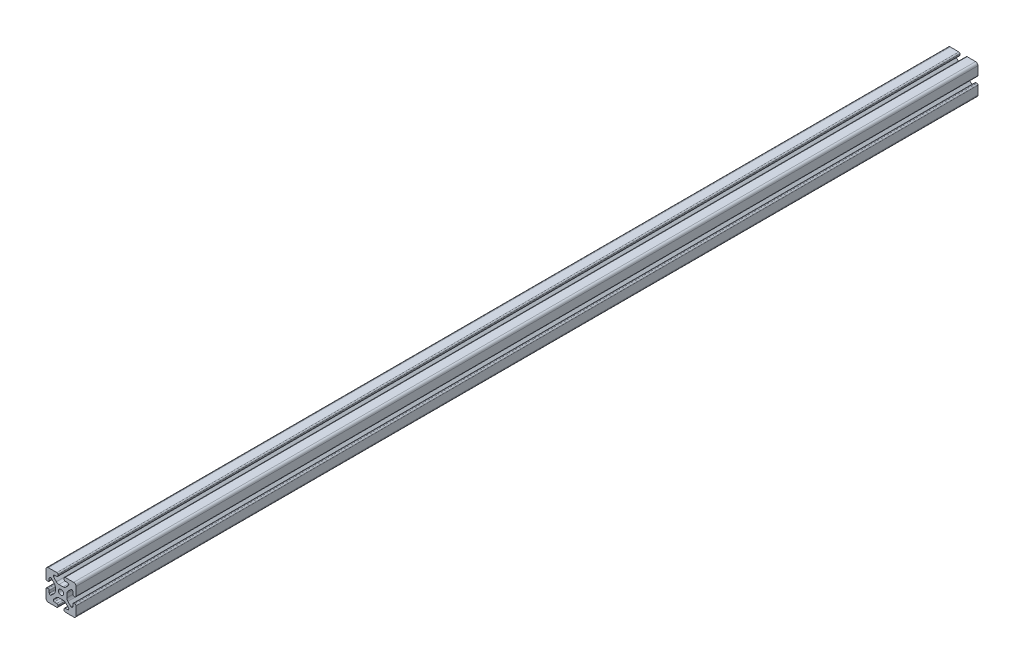
SolidWorks part; units mm, degrees
material "6061 Alloy"
ref_plane "Front Plane" through (0, 0, 0) normal (0, 0, 1) x (1, 0, 0)
ref_plane "Top Plane" through (0, 0, 0) normal (0, 1, 0) x (1, 0, 0)
ref_plane "Right Plane" through (0, 0, 0) normal (1, 0, 0) x (0, 0, -1)
sketch "Sketch1" plane through (0, 0, 0) normal (0, 0, 1) x (1, 0, 0)
  line L0 (0, 19.7407) -> (0, -19.7407) construction
  line L1 (19.0335, 0) -> (-20.7246, 0) construction
  line L2 (-8.715, -15.5246) -> (-5.63, -15.5246)
  line L3 (-10.285, -13.9546) -> (-10.285, -13.4925)
  line L4 (-6.2171, -9.1098) -> (-10.0624, -12.9551)
  line L5 (2.7773, -7.685) -> (-2.7773, -7.685)
  line L6 (10.0624, -12.9551) -> (6.2171, -9.1098)
  line L7 (10.285, -13.9546) -> (10.285, -13.4925)
  line L8 (5.63, -15.5246) -> (8.715, -15.5246)
  line L9 (4.06, -18.43) -> (4.06, -17.0946)
  line L10 (-4.06, -18.43) -> (-4.06, -17.0946)
  line L11 (15.68, -8.7154) -> (15.68, -5.63)
  line L12 (-14.11, -10.2854) -> (-13.8169, -10.2854)
  line L13 (20, -16.83) -> (20, -5.63)
  line L14 (20, 5.63) -> (20, 13.0011)
  line L15 (-16.83, 20) -> (-5.63, 20)
  line L16 (5.63, 20) -> (12.9796, 20)
  line L18 (-8.715, 15.5246) -> (-5.63, 15.5246)
  line L19 (-20, -17.0184) -> (-20, -5.7579)
  line L20 (-20, 5.573) -> (-20, 13.0045)
  line L21 (-15.68, -8.7154) -> (-15.68, -5.7579)
  line L23 (-16.6746, -20) -> (-5.63, -20)
  line L24 (5.63, -20) -> (13, -20)
  line L53 (14.11, -10.2854) -> (13.6201, -10.2854)
  line L54 (13.1637, -9.947) -> (9.0762, -5.8595)
  line L55 (7.685, -2.5008) -> (7.685, 2.5008)
  line L56 (9.0762, 5.8595) -> (13.2795, 10.0628)
  line L57 (13.8169, 10.2854) -> (14.11, 10.2854)
  line L58 (15.68, 8.7154) -> (15.68, 5.63)
  line L59 (17.25, 4.06) -> (18.43, 4.06)
  line L61 (20, 13.0011) -> (20, 16.83)
  line L62 (16.83, 20) -> (12.9796, 20)
  line L64 (4.06, 18.43) -> (4.06, 17.0946)
  line L65 (5.63, 15.5246) -> (8.715, 15.5246)
  line L66 (10.285, 13.9546) -> (10.285, 13.4925)
  line L67 (10.0624, 12.9551) -> (6.2171, 9.1098)
  line L68 (2.7773, 7.685) -> (-2.7773, 7.685)
  line L69 (-6.2171, 9.1098) -> (-10.0624, 12.9551)
  line L70 (-10.285, 13.4925) -> (-10.285, 13.9546)
  line L72 (-4.06, 17.0946) -> (-4.06, 18.43)
  line L75 (-20, 16.83) -> (-20, 13.0045)
  line L77 (-18.43, 4.003) -> (-17.25, 4.003)
  line L78 (-15.68, 5.573) -> (-15.68, 8.4757)
  line L79 (-14.0552, 10.0447) -> (-13.7199, 10.033)
  line L80 (-13.0405, 9.8238) -> (-9.0762, 5.8595)
  line L81 (-7.685, 2.5008) -> (-7.685, -2.5008)
  line L82 (-9.0762, -5.8595) -> (-13.2795, -10.0628)
  line L85 (-17.25, -4.1204) -> (-18.43, -4.1204)
  line L100 (13, -20) -> (16.83, -20)
  line L103 (18.43, -4.06) -> (17.25, -4.06)
  arc A0 (-5.63, -15.5246) -> (-4.06, -17.0946) centre (-5.63, -17.0946) cw
  arc A1 (-8.715, -15.5246) -> (-10.285, -13.9546) centre (-8.715, -13.9546) cw
  arc A2 (-10.285, -13.4925) -> (-10.0624, -12.9551) centre (-9.525, -13.4925) cw
  arc A3 (-6.2171, -9.1098) -> (-2.7773, -7.685) centre (-2.7773, -12.5496) cw
  arc A4 (2.7773, -7.685) -> (6.2171, -9.1098) centre (2.7773, -12.5496) cw
  arc A5 (10.0624, -12.9551) -> (10.285, -13.4925) centre (9.525, -13.4925) cw
  arc A6 (10.285, -13.9546) -> (8.715, -15.5246) centre (8.715, -13.9546) cw
  arc A7 (4.06, -17.0946) -> (5.63, -15.5246) centre (5.63, -17.0946) cw
  arc A8 (5.63, -20) -> (4.06, -18.43) centre (5.63, -18.43) cw
  arc A9 (-4.06, -18.43) -> (-5.63, -20) centre (-5.63, -18.43) cw
  circle A45 centre (0, 0) radius 3.4
  arc A46 (17.25, -4.06) -> (15.68, -5.63) centre (17.25, -5.63) ccw
  arc A47 (14.11, -10.2854) -> (15.68, -8.7154) centre (14.11, -8.7154) ccw
  arc A48 (13.1637, -9.947) -> (13.6201, -10.2854) centre (13.8117, -9.55) ccw
  arc A49 (7.685, -2.5008) -> (9.0762, -5.8595) centre (12.435, -2.5008) ccw
  arc A50 (9.0762, 5.8595) -> (7.685, 2.5008) centre (12.435, 2.5008) ccw
  arc A51 (13.8169, 10.2854) -> (13.2795, 10.0628) centre (13.8169, 9.5254) ccw
  arc A52 (15.68, 8.7154) -> (14.11, 10.2854) centre (14.11, 8.7154) ccw
  arc A53 (15.68, 5.63) -> (17.25, 4.06) centre (17.25, 5.63) ccw
  arc A54 (18.43, 4.06) -> (20, 5.63) centre (18.43, 5.63) ccw
  arc A55 (20, 16.83) -> (16.83, 20) centre (16.83, 16.83) ccw
  arc A56 (5.63, 20) -> (4.06, 18.43) centre (5.63, 18.43) ccw
  arc A57 (4.06, 17.0946) -> (5.63, 15.5246) centre (5.63, 17.0946) ccw
  arc A58 (10.285, 13.9546) -> (8.715, 15.5246) centre (8.715, 13.9546) ccw
  arc A59 (10.0624, 12.9551) -> (10.285, 13.4925) centre (9.525, 13.4925) ccw
  arc A60 (2.7773, 7.685) -> (6.2171, 9.1098) centre (2.7773, 12.5496) ccw
  arc A61 (-6.2171, 9.1098) -> (-2.7773, 7.685) centre (-2.7773, 12.5496) ccw
  arc A62 (-10.285, 13.4925) -> (-10.0624, 12.9551) centre (-9.525, 13.4925) ccw
  arc A63 (-8.715, 15.5246) -> (-10.285, 13.9546) centre (-8.715, 13.9546) ccw
  arc A64 (-5.63, 15.5246) -> (-4.06, 17.0946) centre (-5.63, 17.0946) ccw
  arc A65 (-4.06, 18.43) -> (-5.63, 20) centre (-5.63, 18.43) ccw
  arc A66 (-16.83, 20) -> (-20, 16.83) centre (-16.83, 16.83) ccw
  arc A67 (-20, 5.573) -> (-18.43, 4.003) centre (-18.43, 5.573) ccw
  arc A68 (-17.25, 4.003) -> (-15.68, 5.573) centre (-17.25, 5.573) ccw
  arc A69 (-14.0552, 10.0447) -> (-15.68, 8.4757) centre (-14.11, 8.4757) ccw
  arc A70 (-13.0405, 9.8238) -> (-13.7199, 10.033) centre (-13.5779, 9.2864) ccw
  arc A71 (-7.685, 2.5008) -> (-9.0762, 5.8595) centre (-12.435, 2.5008) ccw
  arc A72 (-9.0762, -5.8595) -> (-7.685, -2.5008) centre (-12.435, -2.5008) ccw
  arc A73 (-13.8169, -10.2854) -> (-13.2795, -10.0628) centre (-13.8169, -9.5254) ccw
  arc A74 (-15.68, -8.7154) -> (-14.11, -10.2854) centre (-14.11, -8.7154) ccw
  arc A75 (-15.68, -5.7579) -> (-17.25, -4.1204) centre (-17.2485, -5.6904) ccw
  arc A76 (-18.43, -4.1204) -> (-20, -5.7579) centre (-18.4315, -5.6904) ccw
  arc A77 (-20, -17.0184) -> (-16.6746, -20) centre (-16.8354, -16.8341) ccw
  arc A88 (16.83, -20) -> (20, -16.83) centre (16.83, -16.83) ccw
  arc A89 (20, -5.63) -> (18.43, -4.06) centre (18.43, -5.63) ccw
  dimension "D2" = 6.8
  dimension "D7" = 20.57
  dimension "D1" = 40
  dimension "D3" = 4.32
  dimension "D4" = 15.37
  dimension "D5" = 20
  dimension "D6" = 4.32
  dimension "D9" = 15.37
extrude "Extrude1" add sketch "Sketch1" against normal blind 1200
